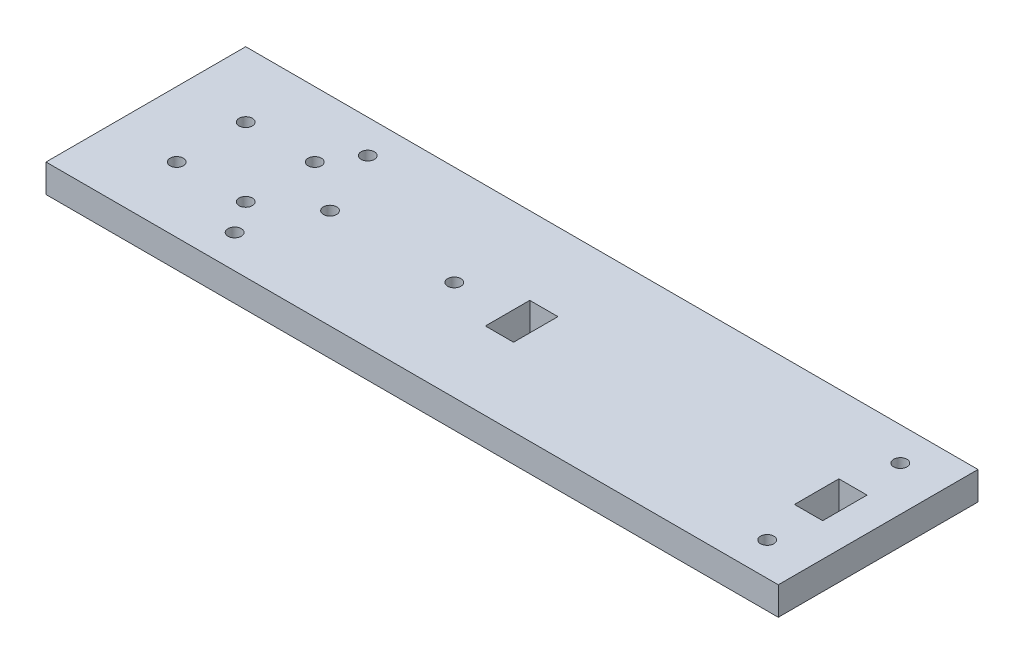
SolidWorks part; units mm, degrees
material "Balsa"
ref_plane "Front Plane" through (0, 0, 0) normal (0, 0, 1) x (1, 0, 0)
ref_plane "Top Plane" through (0, 0, 0) normal (0, 1, 0) x (1, 0, 0)
ref_plane "Right Plane" through (0, 0, 0) normal (1, 0, 0) x (0, 0, -1)
sketch "Sketch1" plane through (0, 0, 0) normal (0, 1, 0) x (1, 0, 0)
  line L0 (14.7218, 14.7218) -> (30.2782, 30.2782)
  line L1 (0, 0) -> (165, 0)
  line L2 (0, 0) -> (0, 45)
  line L3 (0, 45) -> (165, 45)
  line L4 (165, 0) -> (165, 45)
  line L5 (14.7218, 30.2782) -> (30.2782, 14.7218)
  line L6 (22.5, 22.5) -> (22.5, 45) construction
  line L7 (22.5, 22.5) -> (0, 22.5) construction
  line L8 (41.5, 28) -> (69.5, 28)
  line L9 (69.5, 28) -> (69.5, 26)
  line L10 (41.5, 28) -> (41.5, 26)
  line L11 (41.5, 19) -> (41.5, 17)
  line L12 (41.5, 17) -> (69.5, 17)
  line L13 (69.5, 17) -> (69.5, 19)
  line L14 (41.5, 22.5) -> (69.5, 22.5) construction
  line L15 (155, 7.5) -> (155, 37.5) construction
  line L16 (87.85, 27.5) -> (81.5, 27.5)
  line L17 (87.85, 27.5) -> (87.85, 17.5)
  line L18 (87.85, 17.5) -> (81.5, 17.5)
  line L19 (81.5, 27.5) -> (81.5, 17.5)
  line L20 (151.15, 27.5) -> (157.5, 27.5)
  line L21 (151.15, 27.5) -> (151.15, 17.5)
  line L22 (151.15, 17.5) -> (157.5, 17.5)
  line L23 (157.5, 27.5) -> (157.5, 17.5)
  line L24 (155, 7.5) -> (35, 7.5) construction
  line L25 (79, 4) -> (79, 41)
  line L26 (161, 4) -> (79, 4)
  line L27 (161, 4) -> (161, 41)
  line L28 (161, 41) -> (79, 41)
  line L29 (4, 4) -> (4, 41)
  line L30 (75, 41) -> (75, 4)
  line L31 (75, 4) -> (4, 4)
  line L32 (75, 41) -> (4, 41)
  circle A0 centre (14.7218, 30.2782) radius 1.5
  circle A1 centre (14.7218, 14.7218) radius 1.5
  circle A2 centre (30.2782, 30.2782) radius 1.5
  circle A3 centre (30.2782, 14.7218) radius 1.5
  circle A4 centre (22.5, 22.5) radius 14.5
  arc A5 (41.5, 26) -> (41.5, 19) centre (41.5, 22.5) ccw
  arc A6 (69.5, 26) -> (69.5, 19) centre (69.5, 22.5) cw
  circle A7 centre (41.5, 22.5) radius 1.5
  circle A8 centre (69.5, 22.5) radius 1.5
  circle A9 centre (155, 7.5) radius 1.5
  circle A10 centre (155, 37.5) radius 1.5
  circle A11 centre (35, 37.5) radius 1.5
  circle A12 centre (35, 7.5) radius 1.5
  point P13 (0, 22.5)
  point P15 (22.5, 22.5)
  point P17 (22.5, 22.5)
  point P48 (155, 22.5)
  point P49 (165, 22.5)
  dimension "D1" = 3
  dimension "D3" = 29
  dimension "D8" = 7
  dimension "D9" = 19
  dimension "D14" = 3
  dimension "D2" = 22
  dimension "D4" = 45
  dimension "D5" = 59
  dimension "D6" = 28
  dimension "D7" = 2
  dimension "D10" = 6.35
  dimension "D11" = 76
  dimension "D12" = 10
  dimension "D13" = 5
  dimension "D15" = 120
  dimension "D16" = 165
  dimension "D17" = 30
  dimension "D18" = 10
  dimension "D19" = 4
  dimension "D20" = 4
  dimension "D21" = 4
  dimension "D22" = 4
  dimension "D23" = 4
  dimension "D24" = 82
extrude "Boss-Extrude1" add sketch "Sketch1" along normal blind 6.35
